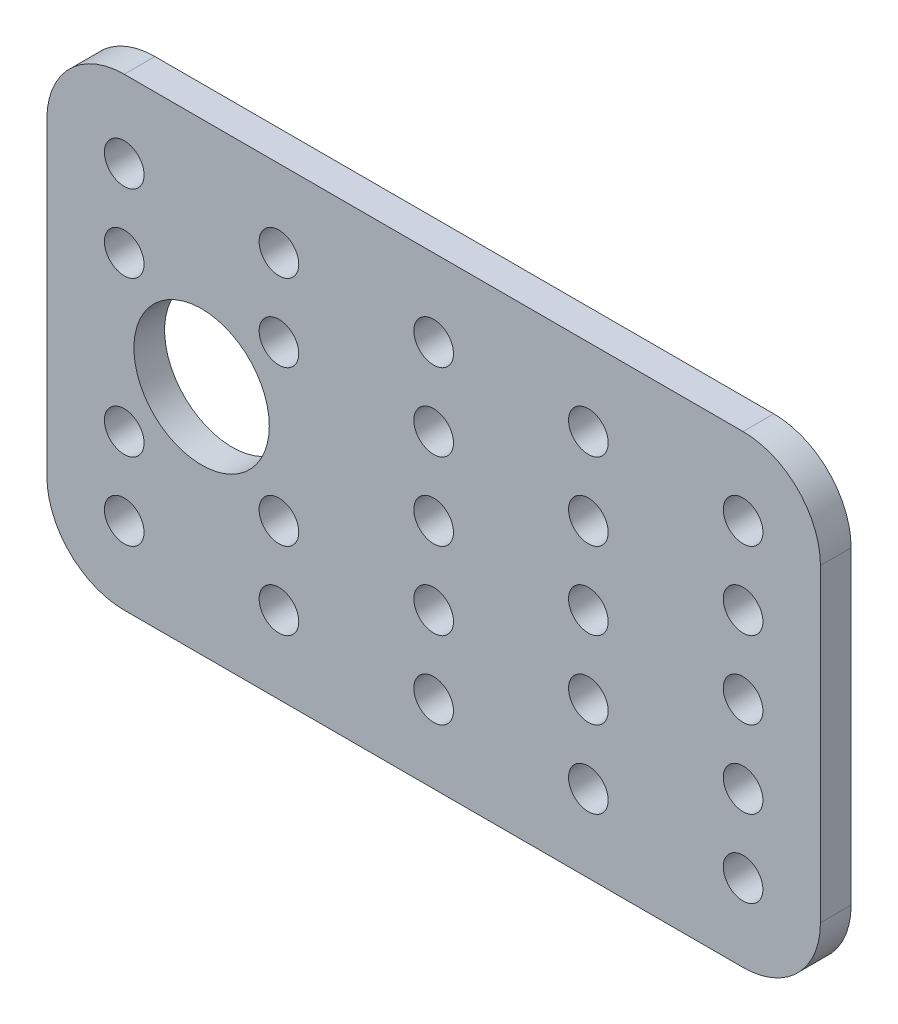
SolidWorks part; units mm, degrees
ref_plane "Front Plane" through (0, 0, 0) normal (0, 0, 1) x (1, 0, 0)
ref_plane "Top Plane" through (0, 0, 0) normal (0, 1, 0) x (1, 0, 0)
ref_plane "Right Plane" through (0, 0, 0) normal (1, 0, 0) x (0, 0, -1)
sketch "Sketch1" plane through (0, 0, 0) normal (0, 0, 1) x (1, 0, 0)
  line L0 (0, 0) -> (-50000, 0) construction
  line L1 (40, -24) -> (-40, -24)
  line L2 (40, -24) -> (40, 24)
  line L3 (40, 24) -> (-40, 24)
  line L4 (-40, -24) -> (-40, 24)
  line L5 (40, -24) -> (-40, 24) construction
  line L6 (40, 24) -> (-40, -24) construction
  line L7 (-32, 8) -> (-16, 8) construction
  line L8 (-32, 8) -> (-32, -8) construction
  line L9 (-32, -8) -> (-16, -8) construction
  line L10 (-16, 8) -> (-16, -8) construction
  line L11 (-32, 8) -> (-16, -8) construction
  line L12 (-32, -8) -> (-16, 8) construction
  line L13 (-32, 16) -> (-16, 16) construction
  line L14 (-40, 24) -> (-32, 24) construction
  line L15 (-40, 24) -> (-40, 16) construction
  line L16 (-40, 16) -> (-32, 16) construction
  line L17 (-32, 24) -> (-32, 16) construction
  line L18 (-32, 16) -> (-32, 8) construction
  circle A0 centre (-24, 0) radius 7
  circle A1 centre (-32, 8) radius 2.05 construction
  circle A2 centre (-16, 8) radius 2.05 construction
  circle A3 centre (-16, -8) radius 2.05 construction
  circle A4 centre (-32, -8) radius 2.05 construction
  circle A5 centre (-32, 16) radius 2.05
  circle A6 centre (-16, 16) radius 2.05
  circle A7 centre (0, 16) radius 2.05
  circle A8 centre (16, 16) radius 2.05
  circle A9 centre (32, 16) radius 2.05
  circle A10 centre (48, 16) radius 2.05 construction
  circle A11 centre (64, 16) radius 2.05 construction
  circle A12 centre (80, 16) radius 2.05 construction
  circle A13 centre (96, 16) radius 2.05 construction
  circle A14 centre (-16, 8) radius 2.05
  circle A15 centre (0, 8) radius 2.05
  circle A16 centre (16, 8) radius 2.05
  circle A17 centre (32, 8) radius 2.05
  circle A18 centre (48, 8) radius 2.05 construction
  circle A19 centre (64, 8) radius 2.05 construction
  circle A20 centre (80, 8) radius 2.05 construction
  circle A21 centre (96, 8) radius 2.05 construction
  circle A22 centre (-16, 0) radius 2.05 construction
  circle A23 centre (0, 0) radius 2.05
  circle A24 centre (16, 0) radius 2.05
  circle A25 centre (32, 0) radius 2.05
  circle A26 centre (48, 0) radius 2.05 construction
  circle A27 centre (64, 0) radius 2.05 construction
  circle A28 centre (80, 0) radius 2.05 construction
  circle A29 centre (96, 0) radius 2.05 construction
  circle A30 centre (-16, -8) radius 2.05
  circle A31 centre (0, -8) radius 2.05
  circle A32 centre (16, -8) radius 2.05
  circle A33 centre (32, -8) radius 2.05
  circle A34 centre (48, -8) radius 2.05 construction
  circle A35 centre (64, -8) radius 2.05 construction
  circle A36 centre (80, -8) radius 2.05 construction
  circle A37 centre (96, -8) radius 2.05 construction
  circle A38 centre (-16, -16) radius 2.05
  circle A39 centre (0, -16) radius 2.05
  circle A40 centre (16, -16) radius 2.05
  circle A41 centre (32, -16) radius 2.05
  circle A42 centre (48, -16) radius 2.05 construction
  circle A43 centre (64, -16) radius 2.05 construction
  circle A44 centre (80, -16) radius 2.05 construction
  circle A45 centre (96, -16) radius 2.05 construction
  circle A46 centre (-32, 8) radius 2.05
  circle A47 centre (-32, 0) radius 2.05 construction
  circle A48 centre (-32, -8) radius 2.05
  circle A49 centre (-32, -16) radius 2.05
  point P0 (0, 0)
  point P6 (-24, 0)
  dimension "D5" = 4.1
  dimension "D6" = 14
  dimension "D1" = 48
  dimension "D2" = 80
  dimension "D3" = 16
  dimension "D4" = 8
  dimension "D7" = 8
  dimension "D8" = 8
  dimension "D11" = 16
  dimension "D12" = 8
  dimension "D9" = 9
  dimension "D10" = 5
extrude "Boss-Extrude1" add sketch "Sketch1" along normal blind 3.175
fillet "Fillet1" radius 8 4 edges at (40, 24, 1.5875) (40, -24, 1.5875) (-40, -24, 1.5875) (-40, 24, 1.5875)
